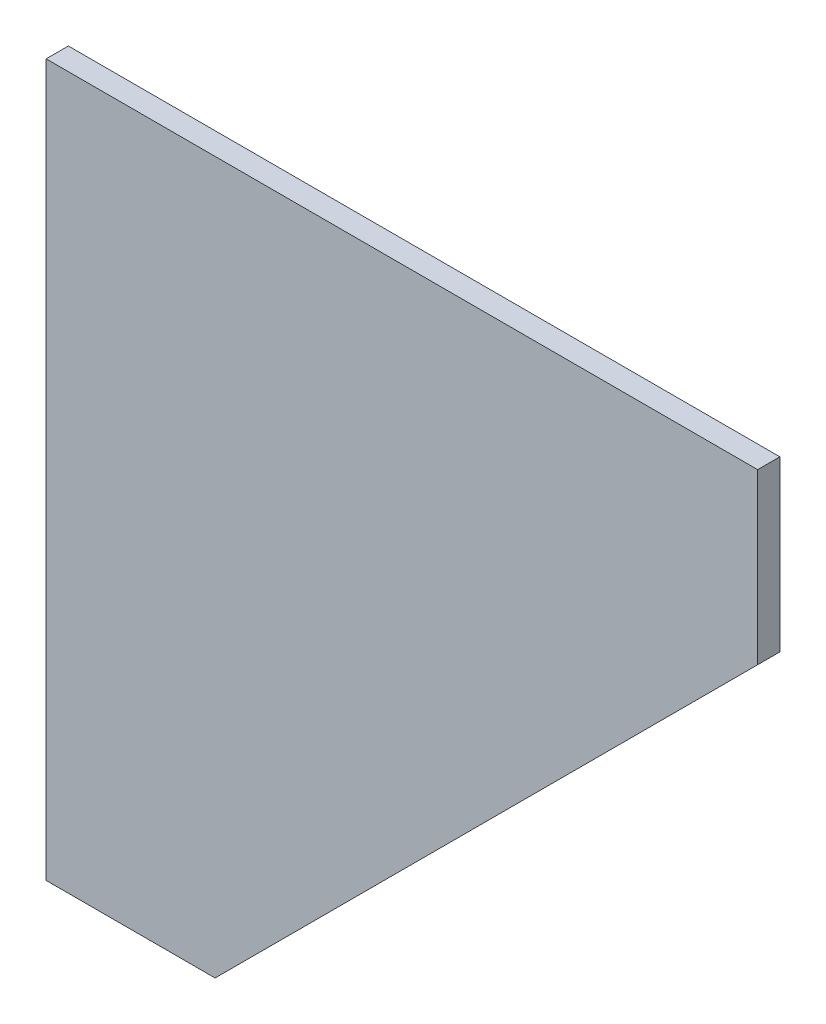
SolidWorks part; units mm, degrees
ref_plane "Front Plane" through (0, 0, 0) normal (0, 0, 1) x (1, 0, 0)
ref_plane "Top Plane" through (0, 0, 0) normal (0, 1, 0) x (1, 0, 0)
ref_plane "Right Plane" through (0, 0, 0) normal (1, 0, 0) x (0, 0, -1)
sketch "Sketch1" plane through (0, 0, 0) normal (0, 0, 1) x (1, 0, 0)
  line L0 (0, 0) -> (0, 101.6)
  line L1 (0, 101.6) -> (101.6, 101.6)
  line L2 (101.6, 101.6) -> (101.6, 77.47)
  line L5 (24.13, 0) -> (0, 0)
  line L6 (24.13, 0) -> (101.6, 77.47)
  dimension "D1" = 24.13
  dimension "D2" = 24.13
  dimension "D3" = 101.6
  dimension "D4" = 101.6
extrude "Boss-Extrude1" add sketch "Sketch1" along normal blind 3.175
sketch "Sketch2" plane through (0, 0, 3.175) normal (0, 0, 1) x (1, 0, 0)
  line L0 (101.6, 101.6) -> (0, 101.6) construction
  line L1 (0, 101.6) -> (0, 0) construction
  circle A0 centre (12.7, 88.9) radius 2.4892
  circle A1 centre (12.7, 63.5) radius 2.5496
  circle A3 centre (12.7, 38.1) radius 2.5862
  circle A4 centre (12.7, 12.7) radius 3.0649
  dimension "D1" = 12.7
  dimension "D2" = 25.4
  dimension "D3" = 25.4
  dimension "D4" = 25.4
  dimension "D5" = 12.7
  dimension "D6" = 4.9784
